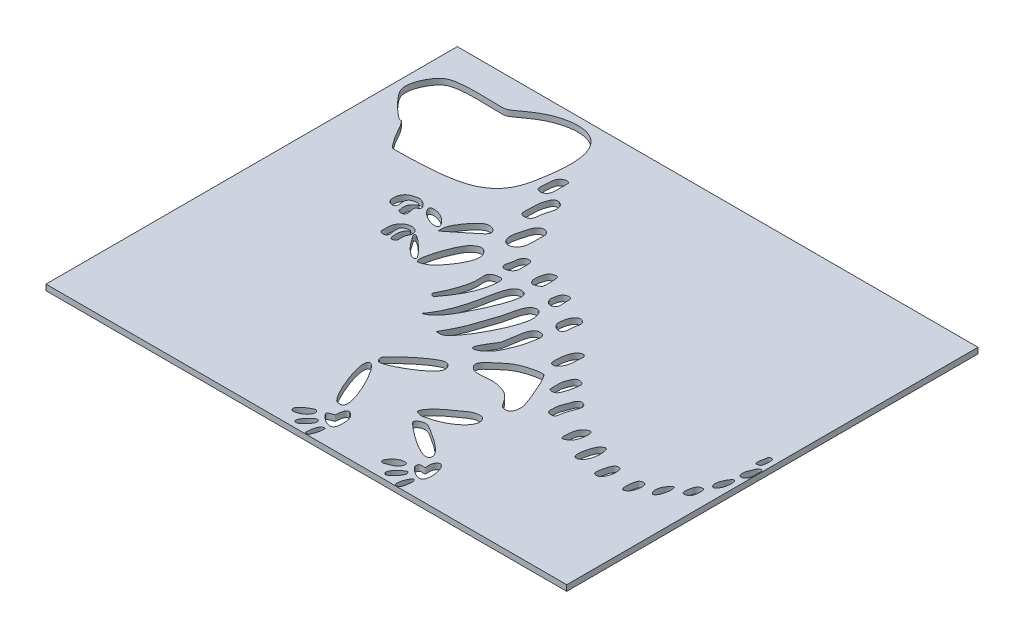
SolidWorks part; units mm, degrees
ref_plane "Front Plane" through (0, 0, 0) normal (0, 0, 1) x (1, 0, 0)
ref_plane "Top Plane" through (0, 0, 0) normal (0, 1, 0) x (1, 0, 0)
ref_plane "Right Plane" through (0, 0, 0) normal (1, 0, 0) x (0, 0, -1)
sketch "Sketch1" plane through (0, 0, 0) normal (0, 1, 0) x (1, 0, 0)
  line L0 (-169.545, -133.35) -> (169.545, 133.35) construction
  line L1 (-169.545, 133.35) -> (169.545, 133.35) construction
  line L2 (-169.545, 133.35) -> (-169.545, -133.35) construction
  line L3 (-169.545, -133.35) -> (169.545, -133.35)
  line L4 (169.545, 133.35) -> (169.545, -133.35)
  line L5 (-169.545, -133.35) -> (-174.8173, -133.35)
  line L6 (-174.8173, -133.35) -> (-174.8173, 138.6223)
  line L7 (-174.8173, 138.6223) -> (169.545, 138.6223)
  line L8 (169.545, 138.6223) -> (169.545, 133.35)
sketch "Sketch2" plane through (0, 0, 0) normal (0, 0, 1) x (1, 0, 0)
  line L0 (0, 0) -> (0, 8.058) construction
  line L1 (-169.545, 0) -> (169.545, 0) construction
sketch "Sketch3" plane through (0, 0, 0) normal (0, 1, 0) x (1, 0, 0)
  line L1 (-159.2597, 106.4446) -> (-159.6747, 106.0436)
  line L2 (-159.2597, 106.4446) -> (-159.6747, 106.0436)
  line L3 (-18.6637, -31.5909) -> (-15.6534, -31.5909)
  line L4 (-18.6637, -31.5909) -> (-15.6534, -31.5909)
  line L9 (-119.1442, 82.4182) -> (-126.9274, 73.6301)
  line L10 (-126.9274, 73.6301) -> (-137.0101, 81.885)
  line L11 (-137.0101, 81.885) -> (-141.0786, 71.6253)
  line L12 (-141.0786, 71.6253) -> (-148.2131, 74.2787)
  line L13 (-150.9255, 77.9344) -> (-138.2469, 90.3926)
  line L14 (-138.2469, 90.3926) -> (-128.1035, 81.885)
  line L15 (-128.1035, 81.885) -> (-119.8998, 89.6232)
  line L16 (-119.8998, 89.6232) -> (-109.2122, 83.2257)
  line L17 (-110.8894, 76.4014) -> (-119.1442, 82.4182)
  line L18 (-119.1442, 82.4182) -> (-126.9274, 73.6301)
  line L19 (-126.9274, 73.6301) -> (-137.0101, 81.885)
  line L20 (-137.0101, 81.885) -> (-141.0786, 71.6253)
  line L21 (-141.0786, 71.6253) -> (-148.2131, 74.2787)
  line L22 (-150.9255, 77.9344) -> (-138.2469, 90.3926)
  line L23 (-138.2469, 90.3926) -> (-128.1035, 81.885)
  line L24 (-128.1035, 81.885) -> (-119.8998, 89.6232)
  line L25 (-119.8998, 89.6232) -> (-109.2122, 83.2257)
  line L26 (-110.8894, 76.4014) -> (-119.1442, 82.4182)
  spline S1 degree 3 poles (-83.4964, 37.7764) (-91.1093, 38.0912) (-92.3245, 36.1465) (-89.8626, 33.2696) (-88.397, 31.9322) (-84.1735, 29.1669) (-80.5001, 28.5844) (-77.9719, 28.5767) (-77.5005, 31.3478) (-83.4964, 37.7764) (-91.1093, 38.0912) (-92.3245, 36.1465) knots -0.416074 -0.374123 -0.145741 0 0.019939 0.179451 0.222926 0.411215 0.451326 0.583926 0.625877 0.854259 1 1.019939 1.179451 1.222926 only from (-91.542, 37.3226) to (-91.542, 37.3226)
  spline S2 degree 3 poles (-83.4964, 37.7764) (-91.1093, 38.0912) (-92.3245, 36.1465) (-89.8626, 33.2696) (-88.397, 31.9322) (-84.1735, 29.1669) (-80.5001, 28.5844) (-77.9719, 28.5767) (-77.5005, 31.3478) (-83.4964, 37.7764) (-91.1093, 38.0912) (-92.3245, 36.1465) knots -0.416074 -0.374123 -0.145741 0 0.019939 0.179451 0.222926 0.411215 0.451326 0.583926 0.625877 0.854259 1 1.019939 1.179451 1.222926 only from (-91.542, 37.3226) to (-91.542, 37.3226)
  spline S3 degree 3 poles (-59.7777, 98.3682) (-63.3692, 98.4014) (-66.441, 95.0319) (-66.8153, 90.6073) (-67.2838, 84.4572) (-65.5283, 82.7312) (-60.9484, 82.8502) (-59.7732, 86.5836) (-59.8732, 90.2765) (-59.6775, 94.7624) (-59.7777, 98.3682) (-63.3692, 98.4014) (-66.441, 95.0319) knots -0.33571 -0.193808 -0.158463 0 0.042191 0.153707 0.286878 0.31643 0.449229 0.62682 0.66429 0.806192 0.841537 1 1.042191 1.153707 1.286878 only from (-64.4656, 97.0494) to (-64.4656, 97.0494)
  spline S4 degree 3 poles (-59.7777, 98.3682) (-63.3692, 98.4014) (-66.441, 95.0319) (-66.8153, 90.6073) (-67.2838, 84.4572) (-65.5283, 82.7312) (-60.9484, 82.8502) (-59.7732, 86.5836) (-59.8732, 90.2765) (-59.6775, 94.7624) (-59.7777, 98.3682) (-63.3692, 98.4014) (-66.441, 95.0319) knots -0.33571 -0.193808 -0.158463 0 0.042191 0.153707 0.286878 0.31643 0.449229 0.62682 0.66429 0.806192 0.841537 1 1.042191 1.153707 1.286878 only from (-64.4656, 97.0494) to (-64.4656, 97.0494)
  spline S5 degree 3 poles (14.2001, -33.8552) (10.7483, -36.7273) (17.6814, -43.0502) (26.9778, -40.4756) (36.8878, -42.7951) (39.9464, -44.1461) (45.1213, -50.7592) (46.4237, -54.2221) (52.7455, -52.611) (53.4487, -47.2061) (51.8775, -41.2033) (43.3886, -20.8685) (39.2427, -19.9873) (27.5948, -22.482) (14.2001, -33.8552) (10.7483, -36.7273) (17.6814, -43.0502) knots -0.34018 -0.233994 -0.198649 0 0.015838 0.142541 0.177932 0.33435 0.366263 0.465147 0.48407 0.536565 0.553469 0.636205 0.65982 0.766006 0.801351 1 1.015838 1.142541 1.177932 only from (14.503, -40.1234) to (14.503, -40.1234)
  spline S6 degree 3 poles (14.2001, -33.8552) (10.7483, -36.7273) (17.6814, -43.0502) (26.9778, -40.4756) (36.8878, -42.7951) (39.9464, -44.1461) (45.1213, -50.7592) (46.4237, -54.2221) (52.7455, -52.611) (53.4487, -47.2061) (51.8775, -41.2033) (43.3886, -20.8685) (39.2427, -19.9873) (27.5948, -22.482) (14.2001, -33.8552) (10.7483, -36.7273) (17.6814, -43.0502) knots -0.34018 -0.233994 -0.198649 0 0.015838 0.142541 0.177932 0.33435 0.366263 0.465147 0.48407 0.536565 0.553469 0.636205 0.65982 0.766006 0.801351 1 1.015838 1.142541 1.177932 only from (14.503, -40.1234) to (14.503, -40.1234)
  spline S7 degree 3 poles (26.0047, -74.9573) (19.169, -82.4247) (22.0563, -84.2759) (24.632, -84.9278) (29.7474, -83.5719) (39.1535, -81.1856) (48.2949, -71.7763) (47.2749, -67.058) (46.5636, -65.1254) (39.3339, -64.7282) (34.6947, -69.4264) (26.0047, -74.9573) (19.169, -82.4247) (22.0563, -84.2759) knots -0.403079 -0.256622 -0.214484 0 0.008451 0.076058 0.110192 0.341341 0.491167 0.514895 0.571534 0.596921 0.743378 0.785516 1 1.008451 1.076058 1.110192 only from (21.2279, -83.7304) to (21.2279, -83.7304)
  spline S8 degree 3 poles (26.0047, -74.9573) (19.169, -82.4247) (22.0563, -84.2759) (24.632, -84.9278) (29.7474, -83.5719) (39.1535, -81.1856) (48.2949, -71.7763) (47.2749, -67.058) (46.5636, -65.1254) (39.3339, -64.7282) (34.6947, -69.4264) (26.0047, -74.9573) (19.169, -82.4247) (22.0563, -84.2759) knots -0.403079 -0.256622 -0.214484 0 0.008451 0.076058 0.110192 0.341341 0.491167 0.514895 0.571534 0.596921 0.743378 0.785516 1 1.008451 1.076058 1.110192 only from (21.2279, -83.7304) to (21.2279, -83.7304)
  spline S9 degree 3 poles (-110.3256, 115.7371) (-118.5309, 110.1193) (-115.9035, 107.1299) (-109.9258, 107.4759) (-111.5274, 104.0614) (-109.8275, 101.823) (-103.0238, 105.7768) (-110.3256, 115.7371) (-118.5309, 110.1193) (-115.9035, 107.1299) knots -0.47372 -0.389255 -0.153946 0 0.145823 0.342645 0.49947 0.52628 0.610745 0.846054 1 1.145823 1.342645 1.49947 only from (-117.0248, 110.3881) to (-117.0248, 110.3881)
  spline S10 degree 3 poles (-110.3256, 115.7371) (-118.5309, 110.1193) (-115.9035, 107.1299) (-109.9258, 107.4759) (-111.5274, 104.0614) (-109.8275, 101.823) (-103.0238, 105.7768) (-110.3256, 115.7371) (-118.5309, 110.1193) (-115.9035, 107.1299) knots -0.47372 -0.389255 -0.153946 0 0.145823 0.342645 0.49947 0.52628 0.610745 0.846054 1 1.145823 1.342645 1.49947 only from (-117.0248, 110.3881) to (-117.0248, 110.3881)
  spline S11 degree 3 poles (1.2232, 31.4999) (0.7793, 27.8057) (0.2826, 24.0052) (2.5706, 20.2577) (6.9873, 21.5919) (7.6543, 25.3189) (7.2509, 29.9545) (7.1684, 32.1224) (5.3971, 32.6148) (1.2232, 31.4999) (0.7793, 27.8057) (0.2826, 24.0052) knots -0.379246 -0.286952 -0.247874 0 0.020185 0.201847 0.395049 0.435786 0.589947 0.620754 0.713048 0.752126 1 1.020185 1.201847 1.395049 only from (0.5283, 25.887) to (0.5283, 25.887)
  spline S12 degree 3 poles (1.2232, 31.4999) (0.7793, 27.8057) (0.2826, 24.0052) (2.5706, 20.2577) (6.9873, 21.5919) (7.6543, 25.3189) (7.2509, 29.9545) (7.1684, 32.1224) (5.3971, 32.6148) (1.2232, 31.4999) (0.7793, 27.8057) (0.2826, 24.0052) knots -0.379246 -0.286952 -0.247874 0 0.020185 0.201847 0.395049 0.435786 0.589947 0.620754 0.713048 0.752126 1 1.020185 1.201847 1.395049 only from (0.5283, 25.887) to (0.5283, 25.887)
  spline S13 degree 3 poles (-16.0328, 34.6718) (-16.763, 31.2747) (-14.4587, 25.8675) (-10.3993, 28.553) (-8.8009, 29.8175) (-8.9683, 38.3568) (-10.0899, 40.6949) (-14.394, 39.5126) (-16.0328, 34.6718) (-16.763, 31.2747) (-14.4587, 25.8675) knots -0.340573 -0.225318 -0.18982 0 0.042268 0.380415 0.444917 0.622786 0.659427 0.774682 0.81018 1 1.042268 1.380415 1.444917 only from (-16.1146, 29.9003) to (-16.1146, 29.9003)
  spline S14 degree 3 poles (4639.1562, 470.9456) (-802.5551, 1234.8923) (-156.2162, 59.4308) (-136.3734, 58.8784) (-112.761, 59.3323) (-91.3623, 61.468) (-75.678, 73.237) (-70.6131, 92.1296) (-68.2354, 123.5234) (-86.3806, 135.7876) (-107.5912, 131.2461) (-120.992, 119.0296) (-128.6914, 118.1657) (-148.4632, 119.9846) (-161.6319, 116.4474) (-167.4615, 108.6964) (-170.1367, 99.8112) (-167.6003, 91.2694) (-157.047, 81.1789) (-149.272, 75.5523) (-81.8694, 49.6716) (-2283.0752, 4597.4651) knots -0.288072 -0.288072 -0.288072 -0.288072 0.018984 0.022838 0.038537 0.169303 0.266188 0.380411 0.50257 0.526559 0.620305 0.67648 0.697256 0.813526 0.832888 0.876336 0.925656 0.937589 0.989212 0.996098 1.065895 1.065895 1.065895 1.065895 only from (-148.2131, 74.2787) to (-150.9255, 77.9344)
  spline S15 degree 3 poles (-2254.8838, 4589.8562) (-177.2639, -390.3034) (-94.8285, 119.6494) (-93.7764, 42.5095) (-186.4575, -71.2057) (-4592.7716, 2283.5264) knots -1.500368 -1.500368 -1.500368 -1.500368 0.274097 0.374097 4.949378 4.949378 4.949378 4.949378 only from (-109.2122, 83.2257) to (-110.8894, 76.4014)
  spline S16 degree 3 poles (-148.2131, 74.2787) (-143.4877, 65.3218) (-138.7147, 58.9436) (-136.3734, 58.8784) (-112.761, 59.3323) (-91.3623, 61.468) (-75.678, 73.237) (-70.6131, 92.1296) (-68.2354, 123.5234) (-86.3806, 135.7876) (-107.5912, 131.2461) (-120.992, 119.0296) (-128.6914, 118.1657) (-148.4632, 119.9846) (-161.6319, 116.4474) (-167.4615, 108.6964) (-170.1367, 99.8112) (-167.6003, 91.2694) (-157.047, 81.1789) (-153.265, 78.442) (-151.3692, 77.5232) (-150.9255, 77.9344) knots 0 0 0 0 0.018984 0.022838 0.038537 0.169303 0.266188 0.380411 0.50257 0.526559 0.620305 0.67648 0.697256 0.813526 0.832888 0.876336 0.925656 0.937589 0.989212 0.996098 1 1 1 1
  spline S17 degree 3 poles (-109.2122, 83.2257) (-97.916, 84.9745) (-94.5838, 101.7048) (-94.4206, 89.7447) (-96.5549, 79.6694) (-110.8894, 76.4014) knots 0 0 0 0 0.274097 0.374097 1 1 1 1
  spline S18 degree 3 poles (-16.0328, 34.6718) (-16.763, 31.2747) (-14.4587, 25.8675) (-10.3993, 28.553) (-8.8009, 29.8175) (-8.9683, 38.3568) (-10.0899, 40.6949) (-14.394, 39.5126) (-16.0328, 34.6718) (-16.763, 31.2747) (-14.4587, 25.8675) knots -0.340573 -0.225318 -0.18982 0 0.042268 0.380415 0.444917 0.622786 0.659427 0.774682 0.81018 1 1.042268 1.380415 1.444917 only from (-16.1146, 29.9003) to (-16.1146, 29.9003)
  spline S19 degree 3 poles (-48.7187, 30.6772) (-52.1964, 32.997) (-59.8929, 25.9145) (-65.3488, 11.1956) (-65.892, 1.1649) (-60.7021, 3.505) (-55.6996, 6.1213) (-43.7455, 22.5717) (-48.7187, 30.6772) (-52.1964, 32.997) (-59.8929, 25.9145) knots -0.711454 -0.234994 -0.157893 0 0.015508 0.139571 0.16247 0.221597 0.288546 0.765006 0.842107 1 1.015508 1.139571 1.16247 only from (-55.8971, 29.561) to (-55.8971, 29.561)
  spline S20 degree 3 poles (-48.7187, 30.6772) (-52.1964, 32.997) (-59.8929, 25.9145) (-65.3488, 11.1956) (-65.892, 1.1649) (-60.7021, 3.505) (-55.6996, 6.1213) (-43.7455, 22.5717) (-48.7187, 30.6772) (-52.1964, 32.997) (-59.8929, 25.9145) knots -0.711454 -0.234994 -0.157893 0 0.015508 0.139571 0.16247 0.221597 0.288546 0.765006 0.842107 1 1.015508 1.139571 1.16247 only from (-55.8971, 29.561) to (-55.8971, 29.561)
  spline S21 degree 3 poles (-5133.9575, -396.9891) (-205.5597, 69.9394) (-188.9531, 116.8601) (-145.5394, 103.6754) (-142.276, 108.3651) (-146.1216, 113.7541) (-202.2219, 105.4595) (128.9994, -34.2822) (-5148.5986, -164.5628) knots -2.980934 -2.980934 -2.980934 -2.980934 0.249242 0.292415 0.431727 0.617682 0.67451 3.961522 3.961522 3.961522 3.961522 only from (-159.6747, 106.0436) to (-159.2597, 106.4446)
  spline S22 degree 3 poles (-159.6747, 106.0436) (-154.5517, 105.9978) (-151.0315, 105.3434) (-145.5394, 103.6754) (-142.276, 108.3651) (-146.1216, 113.7541) (-155.1534, 112.4187) (-156.2051, 109.7963) (-159.2597, 106.4446) knots 0 0 0 0 0.249242 0.292415 0.431727 0.617682 0.67451 1 1 1 1
  spline S23 degree 3 poles (-94.3545, 127.2019) (-106.8747, 125.4021) (-102.5732, 114.6126) (-96.0125, 116.622) (-95.7894, 112.093) (-98.512, 108.507) (-98.1545, 104.575) (-92.0206, 103.476) (-81.5861, 107.858) (-78.4401, 116.3764) (-80.8545, 124.8838) (-85.4986, 127.9278) (-94.3545, 127.2019) (-106.8747, 125.4021) (-102.5732, 114.6126) knots -0.341594 -0.212181 -0.176404 0 0.00701 0.06309 0.075821 0.127314 0.164214 0.194635 0.431528 0.62116 0.658406 0.787819 0.823596 1 1.00701 1.06309 1.075821 only from (-103.8121, 117.7608) to (-103.8121, 117.7608)
  spline S24 degree 3 poles (-94.3545, 127.2019) (-106.8747, 125.4021) (-102.5732, 114.6126) (-96.0125, 116.622) (-95.7894, 112.093) (-98.512, 108.507) (-98.1545, 104.575) (-92.0206, 103.476) (-81.5861, 107.858) (-78.4401, 116.3764) (-80.8545, 124.8838) (-85.4986, 127.9278) (-94.3545, 127.2019) (-106.8747, 125.4021) (-102.5732, 114.6126) knots -0.341594 -0.212181 -0.176404 0 0.00701 0.06309 0.075821 0.127314 0.164214 0.194635 0.431528 0.62116 0.658406 0.787819 0.823596 1 1.00701 1.06309 1.075821 only from (-103.8121, 117.7608) to (-103.8121, 117.7608)
  spline S25 degree 3 poles (53.5634, -113.0402) (51.2421, -112.7967) (51.5228, -117.2525) (58.1989, -121.9472) (62.2943, -120.4276) (63.5727, -111.4641) (59.4982, -104.5919) (55.3217, -107.738) (55.597, -112.8592) (55.9074, -113.1102) (53.5634, -113.0402) (51.2421, -112.7967) (51.5228, -117.2525) knots -0.329975 -0.186168 -0.153171 0 0.017019 0.153169 0.178135 0.249653 0.420162 0.462199 0.670025 0.813832 0.846829 1 1.017019 1.153169 1.178135 only from (51.3879, -114.8039) to (51.3879, -114.8039)
  spline S26 degree 3 poles (53.5634, -113.0402) (51.2421, -112.7967) (51.5228, -117.2525) (58.1989, -121.9472) (62.2943, -120.4276) (63.5727, -111.4641) (59.4982, -104.5919) (55.3217, -107.738) (55.597, -112.8592) (55.9074, -113.1102) (53.5634, -113.0402) (51.2421, -112.7967) (51.5228, -117.2525) knots -0.329975 -0.186168 -0.153171 0 0.017019 0.153169 0.178135 0.249653 0.420162 0.462199 0.670025 0.813832 0.846829 1 1.017019 1.153169 1.178135 only from (51.3879, -114.8039) to (51.3879, -114.8039)
  spline S27 degree 3 poles (116.0178, -50.43) (114.1056, -58.7942) (115.2767, -61.2373) (118.3813, -61.1373) (121.4212, -56.5786) (121.7433, -53.5342) (121.0677, -48.7928) (118.7536, -48.5883) (116.0178, -50.43) (114.1056, -58.7942) (115.2767, -61.2373) knots -0.349445 -0.211705 -0.175039 0 0.017058 0.153519 0.216852 0.587061 0.650555 0.788295 0.824961 1 1.017058 1.153519 1.216852 only from (114.6868, -59.9248) to (114.6868, -59.9248)
  spline S28 degree 3 poles (116.0178, -50.43) (114.1056, -58.7942) (115.2767, -61.2373) (118.3813, -61.1373) (121.4212, -56.5786) (121.7433, -53.5342) (121.0677, -48.7928) (118.7536, -48.5883) (116.0178, -50.43) (114.1056, -58.7942) (115.2767, -61.2373) knots -0.349445 -0.211705 -0.175039 0 0.017058 0.153519 0.216852 0.587061 0.650555 0.788295 0.824961 1 1.017058 1.153519 1.216852 only from (114.6868, -59.9248) to (114.6868, -59.9248)
  spline S29 degree 3 poles (-3.3226, -125.4508) (-4.3848, -130.4052) (-3.9955, -132.8379) (-2.0749, -133.3116) (-0.4685, -129.38) (0.1791, -127.1568) (0.3863, -123.038) (-1.777, -123.942) (-3.3226, -125.4508) (-4.3848, -130.4052) (-3.9955, -132.8379) knots -0.631672 -0.517972 -0.453384 0 0.009256 0.083305 0.118716 0.32796 0.368328 0.482028 0.546616 1 1.009256 1.083305 1.118716 only from (-4.0621, -132.4174) to (-4.0621, -132.4174)
  spline S30 degree 3 poles (-3.3226, -125.4508) (-4.3848, -130.4052) (-3.9955, -132.8379) (-2.0749, -133.3116) (-0.4685, -129.38) (0.1791, -127.1568) (0.3863, -123.038) (-1.777, -123.942) (-3.3226, -125.4508) (-4.3848, -130.4052) (-3.9955, -132.8379) knots -0.631672 -0.517972 -0.453384 0 0.009256 0.083305 0.118716 0.32796 0.368328 0.482028 0.546616 1 1.009256 1.083305 1.118716 only from (-4.0621, -132.4174) to (-4.0621, -132.4174)
  spline S31 degree 3 poles (37.0435, -1.0873) (36.5203, -11.6869) (39.2858, -12.1707) (40.5554, -12.3267) (44.8329, -6.8035) (44.3083, -2.3906) (45.2002, 4.1209) (41.9006, 4.8346) (37.0435, -1.0873) (36.5203, -11.6869) (39.2858, -12.1707) knots -0.440773 -0.268321 -0.222088 0 0.02078 0.187024 0.240791 0.504684 0.559227 0.731679 0.777912 1 1.02078 1.187024 1.240791 only from (37.8964, -11.8619) to (37.8964, -11.8619)
  spline S32 degree 3 poles (37.0435, -1.0873) (36.5203, -11.6869) (39.2858, -12.1707) (40.5554, -12.3267) (44.8329, -6.8035) (44.3083, -2.3906) (45.2002, 4.1209) (41.9006, 4.8346) (37.0435, -1.0873) (36.5203, -11.6869) (39.2858, -12.1707) knots -0.440773 -0.268321 -0.222088 0 0.02078 0.187024 0.240791 0.504684 0.559227 0.731679 0.777912 1 1.02078 1.187024 1.240791 only from (37.8964, -11.8619) to (37.8964, -11.8619)
  spline S33 degree 3 poles (166.2735, 6.6872) (163.446, 7.0482) (162.9479, 3.2565) (161.889, 0.2794) (162.84, -1.9561) (163.8152, -1.4988) (166.092, -0.927) (166.2921, 3.1544) (166.2735, 6.6872) (163.446, 7.0482) (162.9479, 3.2565) knots -0.426404 -0.142769 -0.096583 0 0.033267 0.299406 0.35322 0.517595 0.573596 0.857231 0.903417 1 1.033267 1.299406 1.35322 only from (163.4925, 6.3429) to (163.4925, 6.3429)
  spline S34 degree 3 poles (166.2735, 6.6872) (163.446, 7.0482) (162.9479, 3.2565) (161.889, 0.2794) (162.84, -1.9561) (163.8152, -1.4988) (166.092, -0.927) (166.2921, 3.1544) (166.2735, 6.6872) (163.446, 7.0482) (162.9479, 3.2565) knots -0.426404 -0.142769 -0.096583 0 0.033267 0.299406 0.35322 0.517595 0.573596 0.857231 0.903417 1 1.033267 1.299406 1.35322 only from (163.4925, 6.3429) to (163.4925, 6.3429)
  spline S35 degree 3 poles (150.476, -47.4606) (149.6189, -41.7857) (147.4866, -42.1546) (143.0824, -48.2683) (146.6877, -56.0409) (150.476, -47.4606) (149.6189, -41.7857) (147.4866, -42.1546) knots -0.641609 -0.481952 -0.111593 0 0.035839 0.358391 0.518048 0.888407 1 1.035839 1.358391 1.518048 only from (149.2501, -41.9475) to (149.2501, -41.9475)
  spline S36 degree 3 poles (150.476, -47.4606) (149.6189, -41.7857) (147.4866, -42.1546) (143.0824, -48.2683) (146.6877, -56.0409) (150.476, -47.4606) (149.6189, -41.7857) (147.4866, -42.1546) knots -0.641609 -0.481952 -0.111593 0 0.035839 0.358391 0.518048 0.888407 1 1.035839 1.358391 1.518048 only from (149.2501, -41.9475) to (149.2501, -41.9475)
  spline S37 degree 3 poles (-67.0618, 5.7709) (-76.4091, 14.9391) (-80.9309, 17.2368) (-81.942, 16.6977) (-75.8142, 7.7036) (-72.5906, 5.3163) (-69.3851, 3.0079) (-67.1516, 2.9909) (-67.0618, 5.7709) (-76.4091, 14.9391) (-80.9309, 17.2368) knots -0.317691 -0.218329 -0.185318 0 0.004766 0.042894 0.109883 0.607666 0.682309 0.781671 0.814682 1 1.004766 1.042894 1.109883 only from (-79.9839, 16.7532) to (-79.9839, 16.7532)
  spline S38 degree 3 poles (-67.0618, 5.7709) (-76.4091, 14.9391) (-80.9309, 17.2368) (-81.942, 16.6977) (-75.8142, 7.7036) (-72.5906, 5.3163) (-69.3851, 3.0079) (-67.1516, 2.9909) (-67.0618, 5.7709) (-76.4091, 14.9391) (-80.9309, 17.2368) knots -0.317691 -0.218329 -0.185318 0 0.004766 0.042894 0.109883 0.607666 0.682309 0.781671 0.814682 1 1.004766 1.042894 1.109883 only from (-79.9839, 16.7532) to (-79.9839, 16.7532)
  spline S39 degree 3 poles (17.7444, 21.4282) (16.9206, 16.9256) (16.4497, 10.9496) (21.4059, 8.1953) (24.735, 12.3152) (23.3618, 12.7837) (25.6587, 22.1288) (22.1601, 24.1275) (17.7444, 21.4282) (16.9206, 16.9256) (16.4497, 10.9496) knots -0.286359 -0.200897 -0.171193 0 0.035053 0.315479 0.385774 0.667715 0.713641 0.799103 0.828807 1 1.035053 1.315479 1.385774 only from (16.8039, 15.2944) to (16.8039, 15.2944)
  spline S40 degree 3 poles (17.7444, 21.4282) (16.9206, 16.9256) (16.4497, 10.9496) (21.4059, 8.1953) (24.735, 12.3152) (23.3618, 12.7837) (25.6587, 22.1288) (22.1601, 24.1275) (17.7444, 21.4282) (16.9206, 16.9256) (16.4497, 10.9496) knots -0.286359 -0.200897 -0.171193 0 0.035053 0.315479 0.385774 0.667715 0.713641 0.799103 0.828807 1 1.035053 1.315479 1.385774 only from (16.8039, 15.2944) to (16.8039, 15.2944)
  spline S41 degree 3 poles (-25.4195, -15.9269) (-33.6031, -25.4822) (-33.9723, -25.6936) (-30.7487, -26.1088) (-20.7778, -13.1791) (-9.2036, 12.1292) (-10.7058, 20.0645) (-17.5095, 21.0923) (-20.5334, 13.2032) (-25.4195, -15.9269) (-33.6031, -25.4822) (-33.9723, -25.6936) knots -0.424615 -0.331589 -0.289127 0 0.029367 0.264302 0.315128 0.486805 0.514977 0.575385 0.668411 0.710873 1 1.029367 1.264302 1.315128 only from (-33.7168, -25.5108) to (-33.7168, -25.5108)
  spline S42 degree 3 poles (-25.4195, -15.9269) (-33.6031, -25.4822) (-33.9723, -25.6936) (-30.7487, -26.1088) (-20.7778, -13.1791) (-9.2036, 12.1292) (-10.7058, 20.0645) (-17.5095, 21.0923) (-20.5334, 13.2032) (-25.4195, -15.9269) (-33.6031, -25.4822) (-33.9723, -25.6936) knots -0.424615 -0.331589 -0.289127 0 0.029367 0.264302 0.315128 0.486805 0.514977 0.575385 0.668411 0.710873 1 1.029367 1.264302 1.315128 only from (-33.7168, -25.5108) to (-33.7168, -25.5108)
  spline S43 degree 3 poles (-75.825, 30.4671) (-75.4833, 26.7648) (-76.1791, 26.1328) (-64.5255, 35.5021) (-54.6935, 43.4703) (-60.027, 47.3693) (-66.6386, 45.951) (-73.4093, 36.3888) (-75.825, 30.4671) (-75.4833, 26.7648) (-76.1791, 26.1328) knots -0.366772 -0.182134 -0.143149 0 0.035009 0.350086 0.465041 0.595637 0.633228 0.817866 0.856851 1 1.035009 1.350086 1.465041 only from (-75.6564, 26.7347) to (-75.6564, 26.7347)
  spline S44 degree 3 poles (-75.825, 30.4671) (-75.4833, 26.7648) (-76.1791, 26.1328) (-64.5255, 35.5021) (-54.6935, 43.4703) (-60.027, 47.3693) (-66.6386, 45.951) (-73.4093, 36.3888) (-75.825, 30.4671) (-75.4833, 26.7648) (-76.1791, 26.1328) knots -0.366772 -0.182134 -0.143149 0 0.035009 0.350086 0.465041 0.595637 0.633228 0.817866 0.856851 1 1.035009 1.350086 1.465041 only from (-75.6564, 26.7347) to (-75.6564, 26.7347)
  spline S45 degree 3 poles (154.9833, -40.1852) (155.2078, -43.1713) (157.8214, -42.8592) (159.9962, -40.7546) (160.6569, -40.1318) (160.6628, -34.751) (160.5438, -33.2199) (154.9116, -32.7336) (154.9833, -40.1852) (155.2078, -43.1713) (157.8214, -42.8592) knots -0.330701 -0.330701 0 0 0.323079 0.323079 0.615276 0.615276 0.669299 0.669299 1 1 1.323079 1.323079 1.615276 only from (155.0968, -41.6956) to (155.0968, -41.6956)
  spline S46 degree 3 poles (154.9833, -40.1852) (155.2078, -43.1713) (157.8214, -42.8592) (159.9962, -40.7546) (160.6569, -40.1318) (160.6628, -34.751) (160.5438, -33.2199) (154.9116, -32.7336) (154.9833, -40.1852) (155.2078, -43.1713) (157.8214, -42.8592) knots -0.330701 -0.330701 0 0 0.323079 0.323079 0.615276 0.615276 0.669299 0.669299 1 1 1.323079 1.323079 1.615276 only from (155.0968, -41.6956) to (155.0968, -41.6956)
  spline S47 degree 3 poles (133.0015, -50.5651) (131.5435, -61.333) (138.1694, -59.2019) (139.0313, -51.6054) (137.224, -49.0915) (135.5309, -49.3555) (133.0015, -50.5651) (131.5435, -61.333) (138.1694, -59.2019) knots -0.525379 -0.323564 -0.268503 0 0.044939 0.404455 0.474621 0.676436 0.731497 1 1.044939 1.404455 1.474621 only from (133.8336, -60.4163) to (133.8336, -60.4163)
  spline S48 degree 3 poles (133.0015, -50.5651) (131.5435, -61.333) (138.1694, -59.2019) (139.0313, -51.6054) (137.224, -49.0915) (135.5309, -49.3555) (133.0015, -50.5651) (131.5435, -61.333) (138.1694, -59.2019) knots -0.525379 -0.323564 -0.268503 0 0.044939 0.404455 0.474621 0.676436 0.731497 1 1.044939 1.404455 1.474621 only from (133.8336, -60.4163) to (133.8336, -60.4163)
  spline S49 degree 3 poles (-54.5503, 84.6129) (-56.8248, 80.1217) (-58.1944, 75.7993) (-58.0288, 68.4745) (-58.9869, 62.5105) (-50.5505, 63.678) (-51.4509, 70.7409) (-48.8093, 75.8466) (-48.9572, 82.4788) (-54.5503, 84.6129) (-56.8248, 80.1217) (-58.1944, 75.7993) knots -0.339136 -0.306748 -0.146065 0 0.196712 0.227714 0.310019 0.41906 0.530055 0.660864 0.693252 0.853935 1 1.196712 1.227714 1.310019 only from (-56.5429, 80.409) to (-56.5429, 80.409)
  spline S50 degree 3 poles (-54.5503, 84.6129) (-56.8248, 80.1217) (-58.1944, 75.7993) (-58.0288, 68.4745) (-58.9869, 62.5105) (-50.5505, 63.678) (-51.4509, 70.7409) (-48.8093, 75.8466) (-48.9572, 82.4788) (-54.5503, 84.6129) (-56.8248, 80.1217) (-58.1944, 75.7993) knots -0.339136 -0.306748 -0.146065 0 0.196712 0.227714 0.310019 0.41906 0.530055 0.660864 0.693252 0.853935 1 1.196712 1.227714 1.310019 only from (-56.5429, 80.409) to (-56.5429, 80.409)
  spline S51 degree 3 poles (-48.4575, 50.7091) (-49.2626, 47.1681) (-46.7978, 41.3117) (-43.0237, 41.3188) (-37.4146, 46.0126) (-38.0073, 51.1059) (-37.4862, 62.9135) (-43.2815, 63.5345) (-46.324, 58.818) (-47.0643, 56.0375) (-48.4575, 50.7091) (-49.2626, 47.1681) (-46.7978, 41.3117) knots -0.238976 -0.120095 -0.094711 0 0.018863 0.169766 0.224468 0.511187 0.56694 0.72625 0.761024 0.879905 0.905289 1 1.018863 1.169766 1.224468 only from (-48.5084, 45.499) to (-48.5084, 45.499)
  spline S52 degree 3 poles (-48.4575, 50.7091) (-49.2626, 47.1681) (-46.7978, 41.3117) (-43.0237, 41.3188) (-37.4146, 46.0126) (-38.0073, 51.1059) (-37.4862, 62.9135) (-43.2815, 63.5345) (-46.324, 58.818) (-47.0643, 56.0375) (-48.4575, 50.7091) (-49.2626, 47.1681) (-46.7978, 41.3117) knots -0.238976 -0.120095 -0.094711 0 0.018863 0.169766 0.224468 0.511187 0.56694 0.72625 0.761024 0.879905 0.905289 1 1.018863 1.169766 1.224468 only from (-48.5084, 45.499) to (-48.5084, 45.499)
  spline S53 degree 3 poles (99.4226, -46.306) (96.777, -59.0302) (102.5601, -57.362) (106.7955, -51.0094) (106.0389, -40.492) (101.4375, -43.4666) (99.4226, -46.306) (96.777, -59.0302) (102.5601, -57.362) knots -0.542833 -0.482936 -0.2732 0 0.115049 0.164425 0.457167 0.517064 0.7268 1 1.115049 1.164425 1.457167 only from (99.4683, -57.5719) to (99.4683, -57.5719)
  spline S54 degree 3 poles (99.4226, -46.306) (96.777, -59.0302) (102.5601, -57.362) (106.7955, -51.0094) (106.0389, -40.492) (101.4375, -43.4666) (99.4226, -46.306) (96.777, -59.0302) (102.5601, -57.362) knots -0.542833 -0.482936 -0.2732 0 0.115049 0.164425 0.457167 0.517064 0.7268 1 1.115049 1.164425 1.457167 only from (99.4683, -57.5719) to (99.4683, -57.5719)
  spline S55 degree 3 poles (163.3984, -10.171) (163.7975, -13.4123) (165.9075, -14.4891) (168.2103, -13.268) (169.3048, -9.9441) (168.9278, -6.4947) (169.0667, -2.7932) (165.8653, -3.1153) (165.3231, -6.6557) (163.3984, -10.171) (163.7975, -13.4123) (165.9075, -14.4891) knots -0.29957 -0.180218 -0.150261 0 0.025273 0.227458 0.285534 0.547964 0.592733 0.70043 0.819782 0.849739 1 1.025273 1.227458 1.285534 only from (164.509, -13.7216) to (164.509, -13.7216)
  spline S56 degree 3 poles (163.3984, -10.171) (163.7975, -13.4123) (165.9075, -14.4891) (168.2103, -13.268) (169.3048, -9.9441) (168.9278, -6.4947) (169.0667, -2.7932) (165.8653, -3.1153) (165.3231, -6.6557) (163.3984, -10.171) (163.7975, -13.4123) (165.9075, -14.4891) knots -0.29957 -0.180218 -0.150261 0 0.025273 0.227458 0.285534 0.547964 0.592733 0.70043 0.819782 0.849739 1 1.025273 1.227458 1.285534 only from (164.509, -13.7216) to (164.509, -13.7216)
  spline S57 degree 3 poles (161.3605, -21.8397) (160.4265, -26.1132) (160.9032, -28.4264) (162.615, -30.0315) (164.4985, -27.3078) (165.6961, -26.4673) (166.3158, -20.261) (165.3082, -16.535) (161.3605, -21.8397) (160.4265, -26.1132) (160.9032, -28.4264) knots -0.398326 -0.304359 -0.196628 0 0.019319 0.173869 0.232992 0.551428 0.601674 0.695641 0.803372 1 1.019319 1.173869 1.232992 only from (160.6619, -27.2082) to (160.6619, -27.2082)
  spline S58 degree 3 poles (161.3605, -21.8397) (160.4265, -26.1132) (160.9032, -28.4264) (162.615, -30.0315) (164.4985, -27.3078) (165.6961, -26.4673) (166.3158, -20.261) (165.3082, -16.535) (161.3605, -21.8397) (160.4265, -26.1132) (160.9032, -28.4264) knots -0.398326 -0.304359 -0.196628 0 0.019319 0.173869 0.232992 0.551428 0.601674 0.695641 0.803372 1 1.019319 1.173869 1.232992 only from (160.6619, -27.2082) to (160.6619, -27.2082)
  spline S59 degree 3 poles (-7.5298, -92.0241) (-21.2382, -66.6138) (-25.9456, -76.7543) (-14.8244, -103.3442) (-9.3854, -105.1667) (-6.1821, -104.8261) (-7.5298, -92.0241) (-21.2382, -66.6138) (-25.9456, -76.7543) knots -0.584036 -0.45219 -0.392138 0 0.039948 0.359535 0.415964 0.54781 0.607862 1 1.039948 1.359535 1.415964 only from (-23.3641, -71.6056) to (-23.3641, -71.6056)
  spline S60 degree 3 poles (-7.5298, -92.0241) (-21.2382, -66.6138) (-25.9456, -76.7543) (-14.8244, -103.3442) (-9.3854, -105.1667) (-6.1821, -104.8261) (-7.5298, -92.0241) (-21.2382, -66.6138) (-25.9456, -76.7543) knots -0.584036 -0.45219 -0.392138 0 0.039948 0.359535 0.415964 0.54781 0.607862 1 1.039948 1.359535 1.415964 only from (-23.3641, -71.6056) to (-23.3641, -71.6056)
  spline S61 degree 3 poles (65.1045, -32.7518) (64.0841, -32.9361) (64.188, -40.885) (69.5032, -42.1727) (69.7482, -38.2) (71.0728, -31.8058) (73.6629, -27.5361) (72.5287, -24.6123) (68.03, -22.4386) (65.1045, -32.7518) (64.0841, -32.9361) (64.188, -40.885) knots -0.618451 -0.526367 -0.321115 0 0.007401 0.074012 0.145377 0.175108 0.349517 0.381549 0.473633 0.678885 1 1.007401 1.074012 1.145377 only from (64.1669, -39.2505) to (64.1669, -39.2505)
  spline S62 degree 3 poles (65.1045, -32.7518) (64.0841, -32.9361) (64.188, -40.885) (69.5032, -42.1727) (69.7482, -38.2) (71.0728, -31.8058) (73.6629, -27.5361) (72.5287, -24.6123) (68.03, -22.4386) (65.1045, -32.7518) (64.0841, -32.9361) (64.188, -40.885) knots -0.618451 -0.526367 -0.321115 0 0.007401 0.074012 0.145377 0.175108 0.349517 0.381549 0.473633 0.678885 1 1.007401 1.074012 1.145377 only from (64.1669, -39.2505) to (64.1669, -39.2505)
  spline S63 degree 3 poles (84.5325, -39.6929) (83.7818, -44.1164) (83.0955, -52.0648) (88.7583, -49.4103) (90.7523, -45.2985) (91.1959, -36.2823) (84.5325, -39.6929) (83.7818, -44.1164) (83.0955, -52.0648) knots -0.532893 -0.349963 -0.256566 0 0.149525 0.215411 0.467107 0.650037 0.743434 1 1.149525 1.215411 1.467107 only from (83.6288, -46.3586) to (83.6288, -46.3586)
  spline S64 degree 3 poles (84.5325, -39.6929) (83.7818, -44.1164) (83.0955, -52.0648) (88.7583, -49.4103) (90.7523, -45.2985) (91.1959, -36.2823) (84.5325, -39.6929) (83.7818, -44.1164) (83.0955, -52.0648) knots -0.532893 -0.349963 -0.256566 0 0.149525 0.215411 0.467107 0.650037 0.743434 1 1.149525 1.215411 1.467107 only from (83.6288, -46.3586) to (83.6288, -46.3586)
  spline S65 degree 3 poles (30.012, -86.5198) (23.9065, -89.7847) (30.5529, -96.2273) (48.4864, -109.3804) (54.7253, -102.0458) (39.5391, -91.9832) (30.012, -86.5198) (23.9065, -89.7847) (30.5529, -96.2273) knots -0.565541 -0.186609 -0.125318 0 0.038709 0.348384 0.434459 0.813391 0.874682 1 1.038709 1.348384 1.434459 only from (25.4974, -90.9545) to (25.4974, -90.9545)
  spline S66 degree 3 poles (30.012, -86.5198) (23.9065, -89.7847) (30.5529, -96.2273) (48.4864, -109.3804) (54.7253, -102.0458) (39.5391, -91.9832) (30.012, -86.5198) (23.9065, -89.7847) (30.5529, -96.2273) knots -0.565541 -0.186609 -0.125318 0 0.038709 0.348384 0.434459 0.813391 0.874682 1 1.038709 1.348384 1.434459 only from (25.4974, -90.9545) to (25.4974, -90.9545)
  spline S67 degree 3 poles (9.9775, -13.3304) (0.6836, -30.2048) (7.8703, -28.1108) (12.4686, -23.1134) (16.6292, -13.4903) (18.1767, -9.4193) (19.9409, 2.5233) (15.1984, 2.6829) (10.7579, -0.1086) (10.6453, -7.4221) (8.2581, -18.6449) (9.9775, -13.3304) (0.6836, -30.2048) (7.8703, -28.1108) knots -0.35119 -0.294031 -0.07693 0 0.008075 0.072675 0.09935 0.248152 0.275226 0.343009 0.384518 0.64881 0.705969 0.92307 1 1.008075 1.072675 1.09935 only from (4.0517, -29.1874) to (4.0517, -29.1874)
  spline S68 degree 3 poles (9.9775, -13.3304) (0.6836, -30.2048) (7.8703, -28.1108) (12.4686, -23.1134) (16.6292, -13.4903) (18.1767, -9.4193) (19.9409, 2.5233) (15.1984, 2.6829) (10.7579, -0.1086) (10.6453, -7.4221) (8.2581, -18.6449) (9.9775, -13.3304) (0.6836, -30.2048) (7.8703, -28.1108) knots -0.35119 -0.294031 -0.07693 0 0.008075 0.072675 0.09935 0.248152 0.275226 0.343009 0.384518 0.64881 0.705969 0.92307 1 1.008075 1.072675 1.09935 only from (4.0517, -29.1874) to (4.0517, -29.1874)
  spline S69 degree 3 poles (2141.4856, 4477.0646) (-373.2046, -507.9527) (8.7211, -42.7734) (5.8509, 11.6015) (3.7284, 15.0576) (-3.805, 14.0411) (-4.489, 2.729) (-34.1044, -76.3421) (114.5904, 215.7551) (-2627.9563, -4296.5149) knots -1.083654 -1.083654 -1.083654 -1.083654 0.255506 0.293205 0.367675 0.400617 0.589687 0.651989 2.799812 2.799812 2.799812 2.799812 only from (-15.6534, -31.5909) to (-18.6637, -31.5909)
  spline S70 degree 3 poles (-15.6534, -31.5909) (-10.2854, -31.9146) (6.578, -2.1736) (5.8509, 11.6015) (3.7284, 15.0576) (-3.805, 14.0411) (-4.489, 2.729) (-11.8877, -17.0251) (-10.8873, -17.9698) (-18.6637, -31.5909) knots 0 0 0 0 0.255506 0.293205 0.367675 0.400617 0.589687 0.651989 1 1 1 1
  spline S71 degree 3 poles (-8.7035, -120.2502) (-14.2333, -126.0878) (-14.4025, -129.5655) (-12.9158, -130.3612) (-9.8566, -128.7111) (-6.5461, -124.73) (-6.1158, -122.7955) (-6.403, -121.3879) (-8.7035, -120.2502) (-14.2333, -126.0878) (-14.4025, -129.5655) knots -0.472168 -0.356831 -0.308172 0 0.015962 0.143654 0.194996 0.478035 0.527832 0.643169 0.691828 1 1.015962 1.143654 1.194996 only from (-14.3314, -128.3307) to (-14.3314, -128.3307)
  spline S72 degree 3 poles (-8.7035, -120.2502) (-14.2333, -126.0878) (-14.4025, -129.5655) (-12.9158, -130.3612) (-9.8566, -128.7111) (-6.5461, -124.73) (-6.1158, -122.7955) (-6.403, -121.3879) (-8.7035, -120.2502) (-14.2333, -126.0878) (-14.4025, -129.5655) knots -0.472168 -0.356831 -0.308172 0 0.015962 0.143654 0.194996 0.478035 0.527832 0.643169 0.691828 1 1.015962 1.143654 1.194996 only from (-14.3314, -128.3307) to (-14.3314, -128.3307)
  spline S73 degree 3 poles (-96.158, 32.878) (-92.0135, 33.7446) (-97.9716, 39.8898) (-105.0453, 38.2561) (-109.2626, 36.3399) (-110.0142, 26.5608) (-102.1971, 25.9329) (-105.2392, 33.8289) (-101.4084, 35.9473) (-98.0385, 36.0436) (-96.7658, 35.4294) (-97.2232, 34.5258) (-101.0919, 32.4119) (-100.8791, 28.05) (-100.0765, 24.3886) (-93.7826, 24.7558) (-96.8734, 29.7814) (-96.158, 32.878) (-92.0135, 33.7446) (-97.9716, 39.8898) knots -0.18438 -0.067535 -0.049097 0 0.094857 0.116602 0.217456 0.292257 0.349906 0.420598 0.490923 0.502433 0.531999 0.545686 0.635614 0.729475 0.747476 0.81562 0.932465 0.950903 1 1.094857 1.116602 1.217456 only from (-94.2108, 34.0321) to (-94.2108, 34.0321)
  spline S74 degree 3 poles (-96.158, 32.878) (-92.0135, 33.7446) (-97.9716, 39.8898) (-105.0453, 38.2561) (-109.2626, 36.3399) (-110.0142, 26.5608) (-102.1971, 25.9329) (-105.2392, 33.8289) (-101.4084, 35.9473) (-98.0385, 36.0436) (-96.7658, 35.4294) (-97.2232, 34.5258) (-101.0919, 32.4119) (-100.8791, 28.05) (-100.0765, 24.3886) (-93.7826, 24.7558) (-96.8734, 29.7814) (-96.158, 32.878) (-92.0135, 33.7446) (-97.9716, 39.8898) knots -0.18438 -0.067535 -0.049097 0 0.094857 0.116602 0.217456 0.292257 0.349906 0.420598 0.490923 0.502433 0.531999 0.545686 0.635614 0.729475 0.747476 0.81562 0.932465 0.950903 1 1.094857 1.116602 1.217456 only from (-94.2108, 34.0321) to (-94.2108, 34.0321)
  spline S75 degree 3 poles (-28.375, 21.0946) (-31.8286, 20.175) (-36.0496, 17.5736) (-32.1411, 11.1244) (-39.5877, -7.1075) (-42.3876, -11.2756) (-39.7935, -12.904) (-37.6866, -9.8712) (-27.515, 2.8326) (-25.8026, 19.5361) (-28.375, 21.0946) (-31.8286, 20.175) (-36.0496, 17.5736) knots -0.186231 -0.089391 -0.070768 0 0.025582 0.255816 0.500363 0.535 0.594718 0.623341 0.813769 0.910609 0.929232 1 1.025582 1.255816 1.500363 only from (-32.2964, 19.8153) to (-32.2964, 19.8153)
  spline S76 degree 3 poles (-28.375, 21.0946) (-31.8286, 20.175) (-36.0496, 17.5736) (-32.1411, 11.1244) (-39.5877, -7.1075) (-42.3876, -11.2756) (-39.7935, -12.904) (-37.6866, -9.8712) (-27.515, 2.8326) (-25.8026, 19.5361) (-28.375, 21.0946) (-31.8286, 20.175) (-36.0496, 17.5736) knots -0.186231 -0.089391 -0.070768 0 0.025582 0.255816 0.500363 0.535 0.594718 0.623341 0.813769 0.910609 0.929232 1 1.025582 1.255816 1.500363 only from (-32.2964, 19.8153) to (-32.2964, 19.8153)
  spline S77 degree 3 poles (-33.3619, 31.919) (-34.6647, 30.1321) (-33.1015, 25.7855) (-26.3355, 27.8983) (-26.8287, 34.6853) (-26.2977, 41.0424) (-32.1064, 40.4465) (-33.133, 36.1039) (-33.3619, 31.919) (-34.6647, 30.1321) (-33.1015, 25.7855) knots -0.299754 -0.166898 -0.136922 0 0.023978 0.239776 0.366941 0.500447 0.700246 0.833102 0.863078 1 1.023978 1.239776 1.366941 only from (-34.1568, 28.8211) to (-34.1568, 28.8211)
  spline S78 degree 3 poles (-33.3619, 31.919) (-34.6647, 30.1321) (-33.1015, 25.7855) (-26.3355, 27.8983) (-26.8287, 34.6853) (-26.2977, 41.0424) (-32.1064, 40.4465) (-33.133, 36.1039) (-33.3619, 31.919) (-34.6647, 30.1321) (-33.1015, 25.7855) knots -0.299754 -0.166898 -0.136922 0 0.023978 0.239776 0.366941 0.500447 0.700246 0.833102 0.863078 1 1.023978 1.239776 1.366941 only from (-34.1568, 28.8211) to (-34.1568, 28.8211)
  spline S79 degree 3 poles (43.954, -116.1287) (40.1615, -117.6281) (36.827, -123.6148) (38.5149, -124.7579) (42.3294, -123.13) (46.9913, -122.1728) (47.6054, -116.752) (43.954, -116.1287) (40.1615, -117.6281) (36.827, -123.6148) knots -0.49892 -0.395705 -0.345813 0 0.012393 0.111539 0.161647 0.50108 0.604295 0.654187 1 1.012393 1.111539 1.161647 only from (37.7314, -121.9966) to (37.7314, -121.9966)
  spline S80 degree 3 poles (43.954, -116.1287) (40.1615, -117.6281) (36.827, -123.6148) (38.5149, -124.7579) (42.3294, -123.13) (46.9913, -122.1728) (47.6054, -116.752) (43.954, -116.1287) (40.1615, -117.6281) (36.827, -123.6148) knots -0.49892 -0.395705 -0.345813 0 0.012393 0.111539 0.161647 0.50108 0.604295 0.654187 1 1.012393 1.111539 1.161647 only from (37.7314, -121.9966) to (37.7314, -121.9966)
  spline S81 degree 3 poles (48.6191, -123.1895) (45.8975, -125.5944) (45.0115, -129.0347) (46.1882, -130.6029) (48.943, -129.3146) (51.9481, -126.2701) (53.4583, -122.5287) (52.3156, -120.6443) (48.6191, -123.1895) (45.8975, -125.5944) (45.0115, -129.0347) knots -0.541088 -0.444609 -0.389295 0 0.01462 0.131579 0.176265 0.416787 0.458912 0.555391 0.610705 1 1.01462 1.131579 1.176265 only from (45.2624, -128.0698) to (45.2624, -128.0698)
  spline S82 degree 3 poles (48.6191, -123.1895) (45.8975, -125.5944) (45.0115, -129.0347) (46.1882, -130.6029) (48.943, -129.3146) (51.9481, -126.2701) (53.4583, -122.5287) (52.3156, -120.6443) (48.6191, -123.1895) (45.8975, -125.5944) (45.0115, -129.0347) knots -0.541088 -0.444609 -0.389295 0 0.01462 0.131579 0.176265 0.416787 0.458912 0.555391 0.610705 1 1.01462 1.131579 1.176265 only from (45.2624, -128.0698) to (45.2624, -128.0698)
  spline S83 degree 3 poles (-10.0043, -51.2247) (-19.9599, -61.8478) (-22.3652, -64.6786) (-21.5516, -67.9862) (-15.4431, -67.9808) (6.1856, -55.9317) (6.0249, -48.2583) (3.0525, -44.763) (-10.0043, -51.2247) (-19.9599, -61.8478) (-22.3652, -64.6786) knots -0.449978 -0.362906 -0.316819 0 0.01458 0.131222 0.185136 0.499804 0.550022 0.637094 0.683181 1 1.01458 1.131222 1.185136 only from (-21.569, -63.7434) to (-21.569, -63.7434)
  spline S84 degree 3 poles (-10.0043, -51.2247) (-19.9599, -61.8478) (-22.3652, -64.6786) (-21.5516, -67.9862) (-15.4431, -67.9808) (6.1856, -55.9317) (6.0249, -48.2583) (3.0525, -44.763) (-10.0043, -51.2247) (-19.9599, -61.8478) (-22.3652, -64.6786) knots -0.449978 -0.362906 -0.316819 0 0.01458 0.131222 0.185136 0.499804 0.550022 0.637094 0.683181 1 1.01458 1.131222 1.185136 only from (-21.569, -63.7434) to (-21.569, -63.7434)
  spline S85 degree 3 poles (-84.2148, 13.436) (-81.6413, 15.765) (-83.5597, 20.8961) (-88.3058, 20.7666) (-92.4514, 18.6283) (-94.4753, 15.347) (-94.414, 10.3903) (-94.8067, 7.4382) (-92.9487, 6.8216) (-90.9782, 6.663) (-88.695, 9.3829) (-90.7529, 10.9491) (-89.7894, 17.5768) (-82.6281, 18.1271) (-88.3262, 16.0213) (-87.8648, 6.7181) (-85.5152, 6.5797) (-83.8623, 7.5021) (-83.7195, 10.3193) (-84.2148, 13.436) (-81.6413, 15.765) (-83.5597, 20.8961) knots -0.182293 -0.165555 -0.07093 0 0.047068 0.112312 0.130975 0.22228 0.240811 0.297752 0.310303 0.353767 0.375792 0.508524 0.532567 0.599627 0.665496 0.75207 0.767914 0.817707 0.834445 0.92907 1 1.047068 1.112312 1.130975 only from (-82.3149, 16.7532) to (-82.3149, 16.7532)
  spline S86 degree 3 poles (-84.2148, 13.436) (-81.6413, 15.765) (-83.5597, 20.8961) (-88.3058, 20.7666) (-92.4514, 18.6283) (-94.4753, 15.347) (-94.414, 10.3903) (-94.8067, 7.4382) (-92.9487, 6.8216) (-90.9782, 6.663) (-88.695, 9.3829) (-90.7529, 10.9491) (-89.7894, 17.5768) (-82.6281, 18.1271) (-88.3262, 16.0213) (-87.8648, 6.7181) (-85.5152, 6.5797) (-83.8623, 7.5021) (-83.7195, 10.3193) (-84.2148, 13.436) (-81.6413, 15.765) (-83.5597, 20.8961) knots -0.182293 -0.165555 -0.07093 0 0.047068 0.112312 0.130975 0.22228 0.240811 0.297752 0.310303 0.353767 0.375792 0.508524 0.532567 0.599627 0.665496 0.75207 0.767914 0.817707 0.834445 0.92907 1 1.047068 1.112312 1.130975 only from (-82.3149, 16.7532) to (-82.3149, 16.7532)
  spline S87 degree 3 poles (51.6879, -19.1604) (51.862, -20.2837) (51.9765, -27.6338) (55.37, -27.706) (58.3958, -24.7361) (59.7745, -16.7232) (60.113, -12.9207) (54.8526, -10.9748) (53.4039, -14.9534) (51.6879, -19.1604) (51.862, -20.2837) (51.9765, -27.6338) knots -0.5053 -0.344515 -0.293985 0 0.006885 0.061964 0.094778 0.302212 0.344798 0.4947 0.655485 0.706015 1 1.006885 1.061964 1.094778 only from (51.9543, -26.2149) to (51.9543, -26.2149)
  spline S88 degree 3 poles (51.6879, -19.1604) (51.862, -20.2837) (51.9765, -27.6338) (55.37, -27.706) (58.3958, -24.7361) (59.7745, -16.7232) (60.113, -12.9207) (54.8526, -10.9748) (53.4039, -14.9534) (51.6879, -19.1604) (51.862, -20.2837) (51.9765, -27.6338) knots -0.5053 -0.344515 -0.293985 0 0.006885 0.061964 0.094778 0.302212 0.344798 0.4947 0.655485 0.706015 1 1.006885 1.061964 1.094778 only from (51.9543, -26.2149) to (51.9543, -26.2149)
  spline S89 degree 3 poles (2.7065, -109.5415) (-1.9475, -104.171) (-4.2991, -108.8182) (-4.2255, -112.4598) (-4.4, -112.6635) (-7.4477, -113.7255) (-9.4386, -115.4347) (-1.3072, -122.1526) (3.3704, -119.3634) (3.2785, -114.6986) (2.7065, -109.5415) (-1.9475, -104.171) (-4.2991, -108.8182) knots -0.210292 -0.103953 -0.081595 0 0.224542 0.449658 0.483564 0.554704 0.584878 0.755134 0.789708 0.896047 0.918405 1 1.224542 1.449658 1.483564 only from (0.2896, -107.0538) to (0.2896, -107.0538)
  spline S90 degree 3 poles (2.7065, -109.5415) (-1.9475, -104.171) (-4.2991, -108.8182) (-4.2255, -112.4598) (-4.4, -112.6635) (-7.4477, -113.7255) (-9.4386, -115.4347) (-1.3072, -122.1526) (3.3704, -119.3634) (3.2785, -114.6986) (2.7065, -109.5415) (-1.9475, -104.171) (-4.2991, -108.8182) knots -0.210292 -0.103953 -0.081595 0 0.224542 0.449658 0.483564 0.554704 0.584878 0.755134 0.789708 0.896047 0.918405 1 1.224542 1.449658 1.483564 only from (0.2896, -107.0538) to (0.2896, -107.0538)
  spline S91 degree 3 poles (59.9459, -124.28) (58.396, -123.0484) (56.7101, -125.2424) (54.8201, -129.2268) (55.3522, -132.735) (56.485, -133.368) (59.3904, -131.5461) (59.2405, -128.9557) (59.9459, -124.28) (58.396, -123.0484) (56.7101, -125.2424) knots -0.401194 -0.136756 -0.093332 0 0.045549 0.409938 0.466513 0.554725 0.598806 0.863244 0.906668 1 1.045549 1.409938 1.466513 only from (58.3129, -123.4228) to (58.3129, -123.4228)
  spline S92 degree 3 poles (59.9459, -124.28) (58.396, -123.0484) (56.7101, -125.2424) (54.8201, -129.2268) (55.3522, -132.735) (56.485, -133.368) (59.3904, -131.5461) (59.2405, -128.9557) (59.9459, -124.28) (58.396, -123.0484) (56.7101, -125.2424) knots -0.401194 -0.136756 -0.093332 0 0.045549 0.409938 0.466513 0.554725 0.598806 0.863244 0.906668 1 1.045549 1.409938 1.466513 only from (58.3129, -123.4228) to (58.3129, -123.4228)
  spline S93 degree 3 poles (-20.2946, -119.4655) (-22.357, -122.6958) (-21.5363, -124.444) (-17.8532, -124.4882) (-12.5204, -121.7818) (-11.9194, -116.922) (-13.4067, -115.6733) (-17.0932, -117.4717) (-20.2946, -119.4655) (-22.357, -122.6958) (-21.5363, -124.444) knots -0.34583 -0.301456 -0.033495 0 0.126685 0.18231 0.514705 0.567134 0.65417 0.698544 0.966505 1 1.126685 1.18231 1.514705 only from (-21.8477, -121.9966) to (-21.8477, -121.9966)
  spline S94 degree 3 poles (-20.2946, -119.4655) (-22.357, -122.6958) (-21.5363, -124.444) (-17.8532, -124.4882) (-12.5204, -121.7818) (-11.9194, -116.922) (-13.4067, -115.6733) (-17.0932, -117.4717) (-20.2946, -119.4655) (-22.357, -122.6958) (-21.5363, -124.444) knots -0.34583 -0.301456 -0.033495 0 0.126685 0.18231 0.514705 0.567134 0.65417 0.698544 0.966505 1 1.126685 1.18231 1.514705 only from (-21.8477, -121.9966) to (-21.8477, -121.9966)
  dimension "D1" = 0
  dimension "D2" = 0
  dimension "D3" = 0
  dimension "D4" = 0
  dimension "D5" = 0
  dimension "D6" = 0
  dimension "D7" = 0
  dimension "D8" = 0
  dimension "D9" = 0
  dimension "D10" = 0
  dimension "D11" = 0
  dimension "D12" = 0
  dimension "D13" = 0
  dimension "D14" = 0
  dimension "D15" = 0
  dimension "D16" = 0
  dimension "D17" = 0
  dimension "D18" = 0
  dimension "D19" = 0
  dimension "D20" = 0
  dimension "D21" = 0
  dimension "D22" = 0
  dimension "D23" = 0
  dimension "D24" = 0
  dimension "D25" = 0
  dimension "D26" = 0
  dimension "D27" = 0
  dimension "D28" = 0
  dimension "D29" = 0
  dimension "D30" = 0
  dimension "D31" = 0
  dimension "D32" = 0
  dimension "D33" = 0
  dimension "D34" = 0
  dimension "D35" = 0
  dimension "D36" = 0
  dimension "D37" = 0
  dimension "D38" = 0
  dimension "D39" = 0
  dimension "D40" = 0
  dimension "D41" = 0
  dimension "D42" = 0
  dimension "D43" = 0
  dimension "D44" = 0
  dimension "D45" = 0
  dimension "D46" = 0
extrude "Boss-Extrude1" add sketch "Sketch1" along normal blind 3.81
extrude "Cut-Extrude2" cut sketch "Sketch3" along normal through all
sketch "Sketch4" plane through (0, 3.81, 0) normal (0, 1, 0) x (1, 0, 0)
  line L0 (-150.9255, 77.9344) -> (-148.2131, 74.2787)
  spline S0 degree 3 poles (2652.103, 690.0049) (-631.9356, 925.2757) (-153.5388, 59.3563) (-136.3734, 58.8784) (-112.761, 59.3323) (-91.3623, 61.468) (-75.678, 73.237) (-70.6131, 92.1296) (-68.2354, 123.5234) (-86.3806, 135.7876) (-107.5912, 131.2461) (-120.992, 119.0296) (-128.6914, 118.1657) (-148.4632, 119.9846) (-161.6319, 116.4474) (-167.4615, 108.6964) (-170.1367, 99.8112) (-167.6003, 91.2694) (-157.047, 81.1789) (-149.9266, 76.026) (-99.6154, 56.5169) (-1414.9897, 2797.2552) knots -0.244003 -0.244003 -0.244003 -0.244003 0.018984 0.022838 0.038537 0.169303 0.266188 0.380411 0.50257 0.526559 0.620305 0.67648 0.697256 0.813526 0.832888 0.876336 0.925656 0.937589 0.989212 0.996098 1.055092 1.055092 1.055092 1.055092 only from (-148.2131, 74.2787) to (-150.9255, 77.9344) construction
  spline S1 degree 3 poles (-148.2131, 74.2787) (-143.4877, 65.3218) (-138.7147, 58.9436) (-136.3734, 58.8784) (-112.761, 59.3323) (-91.3623, 61.468) (-75.678, 73.237) (-70.6131, 92.1296) (-68.2354, 123.5234) (-86.3806, 135.7876) (-107.5912, 131.2461) (-120.992, 119.0296) (-128.6914, 118.1657) (-148.4632, 119.9846) (-161.6319, 116.4474) (-167.4615, 108.6964) (-170.1367, 99.8112) (-167.6003, 91.2694) (-157.047, 81.1789) (-153.265, 78.442) (-151.3692, 77.5232) (-150.9255, 77.9344) knots 0 0 0 0 0.018984 0.022838 0.038537 0.169303 0.266188 0.380411 0.50257 0.526559 0.620305 0.67648 0.697256 0.813526 0.832888 0.876336 0.925656 0.937589 0.989212 0.996098 1 1 1 1
extrude "Cut-Extrude3" cut sketch "Sketch4" against normal through all
